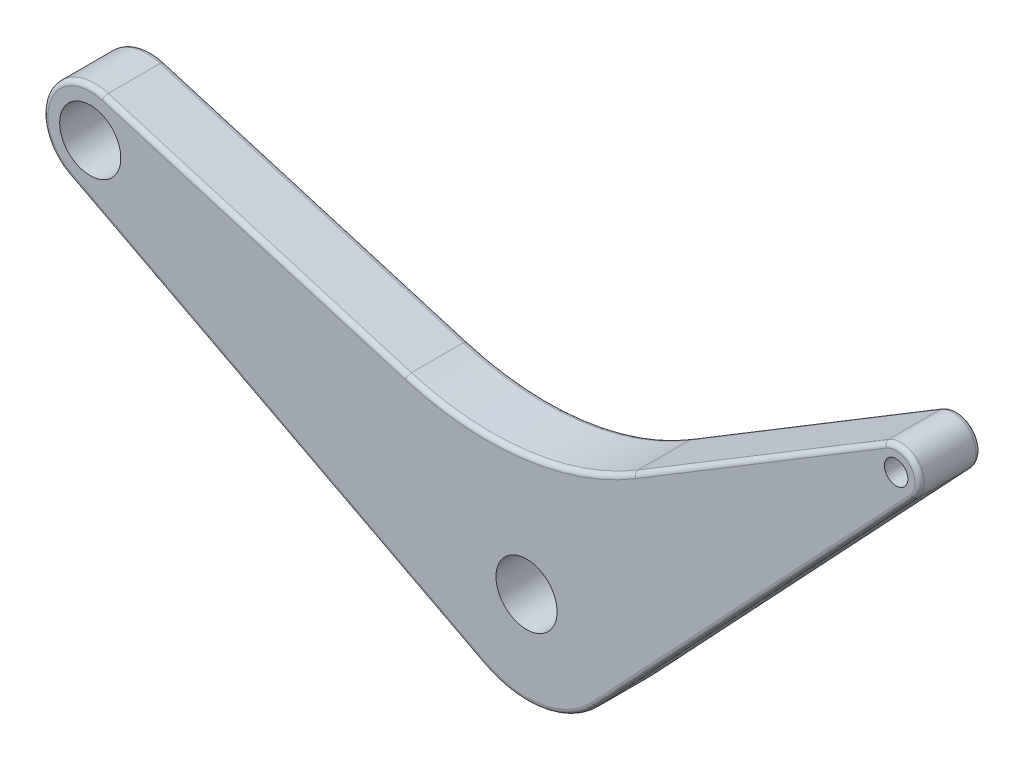
SolidWorks part; units mm, degrees
ref_plane "Front Plane" through (0, 0, 0) normal (0, 0, 1) x (1, 0, 0)
ref_plane "Top Plane" through (0, 0, 0) normal (0, 1, 0) x (1, 0, 0)
ref_plane "Right Plane" through (0, 0, 0) normal (1, 0, 0) x (0, 0, -1)
sketch "Sketch1" plane through (0, 0, 0) normal (0, 0, 1) x (1, 0, 0)
  line L0 (0, 0) -> (-46.4103, 18.6033) construction
  line L1 (0, 0) -> (39.3161, 30.8909) construction
  line L2 (-46.4103, 18.6033) -> (39.3161, 30.8909) construction
  line L3 (-48.7254, 14.1715) -> (-4.6302, -8.8635)
  line L4 (-44.9833, 23.3953) -> (0, 10)
  line L5 (0, 10) -> (38.0209, 33.0292)
  line L6 (41.138, 29.179) -> (7.2878, -6.8475)
  arc A0 (-4.6302, -8.8635) -> (7.2878, -6.8475) centre (0, 0) ccw
  arc A1 (-44.9833, 23.3953) -> (-48.7254, 14.1715) centre (-46.4103, 18.6033) ccw
  arc A3 (41.138, 29.179) -> (38.0209, 33.0292) centre (39.3161, 30.8909) ccw
  circle A4 centre (-46.4103, 18.6033) radius 3.25
  circle A5 centre (39.3161, 30.8909) radius 1.25
  circle A6 centre (0, 0) radius 3.25
  dimension "D1" = 10
  dimension "D2" = 6.5
  dimension "D3" = 20
  dimension "D8" = 2.5
  dimension "D4" = 50
  dimension "D5" = 50
  dimension "D6" = 30
  dimension "D7" = 30
extrude "Boss-Extrude1" add sketch "Sketch1" along normal blind 6.5
fillet "Fillet1" radius 30 1 edges at (0, 10, 3.25)
fillet "Fillet2" radius 0.5 16 edges at (-0.3578, 12.789, 0) (24.694, 24.9572, 0) (41.2591, 32.464, 0) (24.2129, 11.1657, 0) (1.6678, -9.8599, 0) (-26.6778, 2.654, 0) (-51.0435, 20.483, 0) (-0.3578, 12.789, 6.5) (24.694, 24.9572, 6.5) (41.2591, 32.464, 6.5) (24.2129, 11.1657, 6.5) (1.6678, -9.8599, 6.5) (-26.6778, 2.654, 6.5) (-51.0435, 20.483, 6.5) (-28.8602, 18.5941, 0) (-28.8602, 18.5941, 6.5)
sketch "Sketch2" plane through (0, 0, 0) normal (0, 0, 1) x (1, 0, 0)
  circle A0 centre (0, 0) radius 7.5
  circle A1 centre (0, 0) radius 3.25
  dimension "D1" = 15
  dimension "D2" = 6.5
extrude "Boss-Extrude3" add sketch "Sketch2" against normal blind 1.5
fillet "Fillet3" radius 0.5 4 edges at (40.5661, 30.8909, 0) (-43.1603, 18.6033, 0) (7.5, 0, 0) (7.5, 0, -1.5)
scale "缩放比例1" scale about centroid uniform scaling yes scale factor 2
